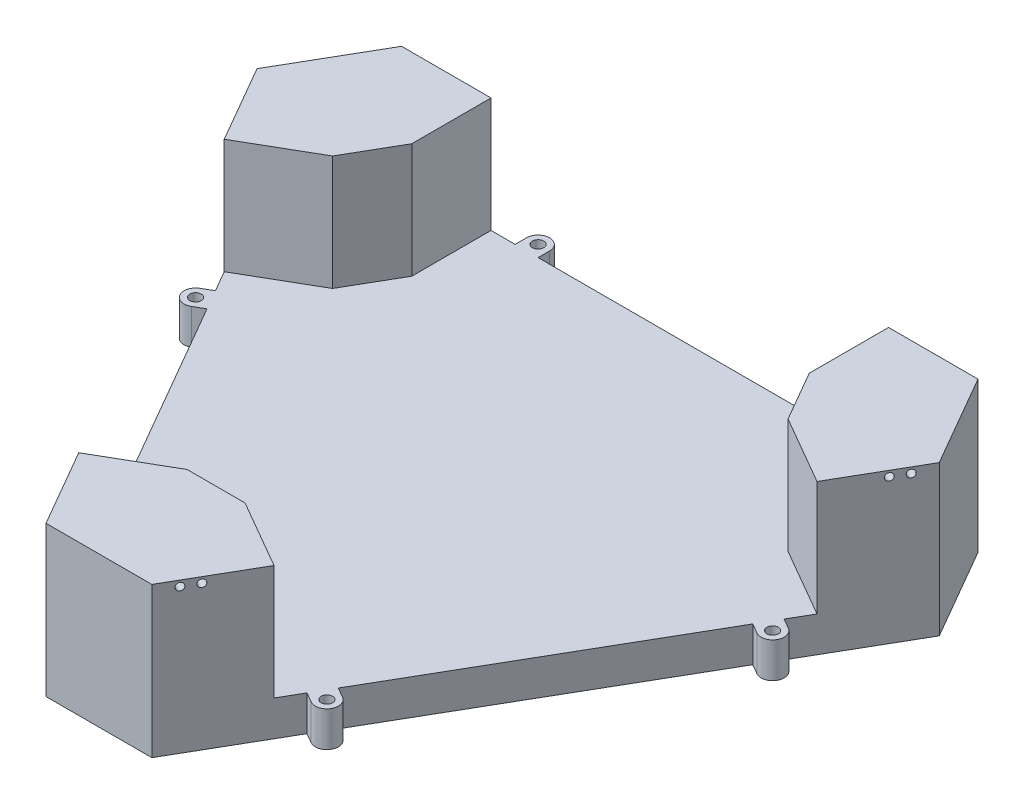
SolidWorks part; units mm, degrees
material "Prusament PETG"
ref_plane "Front Plane" through (0, 0, 0) normal (0, 0, 1) x (1, 0, 0)
ref_plane "Top Plane" through (0, 0, 0) normal (0, 1, 0) x (1, 0, 0)
ref_plane "Right Plane" through (0, 0, 0) normal (1, 0, 0) x (0, 0, -1)
sketch "Sketch1" plane through (0, 0, 0) normal (0, 1, 0) x (1, 0, 0)
  line L3 (-240.2461, 7.855) -> (-236.8299, 13.7721) construction
  line L4 (-120.2366, -188.1733) -> (-7.0596, 7.855) construction
  line L5 (-10.4758, 13.7721) -> (-236.8299, 13.7721) construction
  line L6 (-240.2461, 7.855) -> (-127.0691, -188.1733) construction
  line L7 (-10.4758, 13.7721) -> (-7.0596, 7.855) construction
  line L8 (-120.2366, -188.1733) -> (-127.0691, -188.1733) construction
  line L17 (-236.8299, 13.7721) -> (-10.4758, 13.7721) construction
  line L19 (-278.201, -14.1044) -> (-165.0639, -210.0635) construction
  line L22 (-278.201, -14.1044) -> (-236.7899, 57.6217) construction
  line L24 (-90.4117, 13.7721) -> (-156.894, 13.7721) construction
  line L25 (-156.894, 13.7721) -> (-236.8299, 13.7721) construction
  line L26 (-90.4117, 13.7721) -> (-10.4758, 13.7721) construction
  line L27 (-236.7899, 57.6217) -> (-10.5158, 57.6217) construction
  line L28 (-10.5158, 57.6217) -> (30.8953, -14.1044) construction
  line L29 (30.8953, -14.1044) -> (-82.2418, -210.0635) construction
  line L30 (-82.2418, -210.0635) -> (-165.0639, -210.0635) construction
  line L31 (-236.8299, 13.7721) -> (-156.894, 13.7721) construction
  line L35 (-236.7899, 43.6217) -> (-10.5158, 43.6217)
  line L36 (-240.2461, 7.855) -> (-127.0691, -188.1733) construction
  line L44 (-120.2366, -188.1733) -> (-7.0596, 7.855) construction
  line L47 (-94.3662, -203.0635) -> (18.7709, -7.1044)
  line L48 (18.7709, -7.1044) -> (30.8953, -14.1044) construction
  line L49 (-94.3662, -203.0635) -> (-82.2418, -210.0635) construction
  line L50 (-152.9396, -203.0635) -> (-165.0639, -210.0635) construction
  line L51 (-266.0766, -7.1044) -> (-278.201, -14.1044) construction
  line L52 (-236.7899, 43.6217) -> (-236.7899, 57.6217) construction
  line L53 (-10.5158, 43.6217) -> (-10.5158, 57.6217) construction
  line L54 (18.7709, -7.1044) -> (24.9954, 3.6767)
  line L55 (-10.5158, 43.6217) -> (1.9331, 43.6217)
  line L56 (-94.3662, -203.0635) -> (-100.5906, -213.8446)
  line L57 (-152.9396, -203.0635) -> (-146.7151, -213.8446)
  line L58 (-236.7899, 43.6217) -> (-249.2388, 43.6217)
  line L59 (-266.0766, -7.1044) -> (-272.3011, 3.6767)
  line L60 (-272.3011, 3.6767) -> (-249.2388, 43.6217)
  line L61 (24.9954, 3.6767) -> (1.9331, 43.6217)
  line L62 (-100.5906, -213.8446) -> (-146.7151, -213.8446)
  line L63 (-266.0766, -7.1044) -> (-152.9396, -203.0635)
  circle A0 centre (-123.6529, -55.5154) radius 132.7019 construction
  circle A5 centre (-123.6529, -55.5154) radius 160 construction
  dimension "D1" = 320
  dimension "D3" = 265.4038
  dimension "Distance_of_servo_centre_of_rotation_to_edge" = 14
  dimension "D5" = 82.8221
  dimension "D2" = 30
  dimension "D4" = 90
extrude "Boss-Extrude2" add sketch "Sketch1" along normal blind 5.4 contours L59 L63 L57 L62 L56 L47 L54 L61 L55 L35 L58 L60
sketch "Sketch25" plane through (0, 0, 0) normal (0, -1, 0) x (1, 0, 0)
  line L0 (-272.3011, -3.6767) -> (-249.2388, -43.6217)
  line L1 (-249.2388, -43.6217) -> (1.9331, -43.6217)
  line L2 (1.9331, -43.6217) -> (24.9954, -3.6767)
  line L3 (24.9954, -3.6767) -> (-100.5906, 213.8446)
  line L4 (-100.5906, 213.8446) -> (-146.7151, 213.8446)
  line L5 (-146.7151, 213.8446) -> (-272.3011, -3.6767)
extrude "Boss-Extrude3" add sketch "Sketch25" along normal blind 60
sketch "Sketch26" plane through (-202.6338, 0, 116.9907) normal (-0.866, 0, 0.5) x (0.5, 0, 0.866)
  line L0 (-13.7487, 5.4) -> (-13.7487, -60) construction
  line L1 (111.8373, 5.4) -> (-139.3347, 5.4) construction
  line L2 (111.8373, -60) -> (-139.3347, -60) construction
  line L3 (-38.7487, -15) -> (11.2513, -15)
  line L4 (-38.7487, -15) -> (-38.7487, -55)
  line L5 (11.2513, -15) -> (11.2513, -55)
  line L6 (-38.7487, -55) -> (11.2513, -55)
  line L7 (-38.7487, -15) -> (11.2513, -55) construction
  line L8 (11.2513, -15) -> (-38.7487, -55) construction
  point P6 (-13.7487, -15)
  point P7 (-13.7487, -35)
  dimension "D1" = 50
  dimension "D2" = 40
  dimension "D3" = 5
sketch "Sketch27" plane through (0, 5.4, 0) normal (0, 1, 0) x (1, 0, 0)
  line L0 (-272.3011, 3.6767) -> (-249.2388, 43.6217) construction
  line L1 (-249.2388, 43.6217) -> (1.9331, 43.6217) construction
  line L2 (1.9331, 43.6217) -> (24.9954, 3.6767) construction
  line L3 (24.9954, 3.6767) -> (-100.5906, -213.8446) construction
  line L4 (-100.5906, -213.8446) -> (-146.7151, -213.8446) construction
  line L5 (-146.7151, -213.8446) -> (-272.3011, 3.6767) construction
  line L6 (1.9013, 3.6767) -> (-112.1376, -193.8446)
  line L7 (-112.1376, -193.8446) -> (-135.1681, -193.8446)
  line L8 (-135.1681, -193.8446) -> (-249.2071, 3.6767)
  line L9 (-249.2071, 3.6767) -> (-237.6918, 23.6217)
  line L10 (-237.6918, 23.6217) -> (-9.6139, 23.6217)
  line L11 (-9.6139, 23.6217) -> (1.9013, 3.6767)
  dimension "D1" = 20
sketch "Sketch28" plane through (-202.6338, 0, 116.9907) normal (-0.866, 0, 0.5) x (0.5, 0, 0.866)
  line L0 (95.8884, 2.9) -> (102.8884, 2.9) construction
  line L1 (95.8884, 2.9) -> (86.9395, 2.9) construction
  line L2 (102.8884, 2.9) -> (111.8373, 2.9) construction
  line L3 (111.8373, 5.4) -> (-139.3347, 5.4) construction
  line L4 (111.8373, 5.4) -> (111.8373, -60) construction
  circle A0 centre (95.8884, 2.9) radius 1.6
  circle A1 centre (102.8884, 2.9) radius 1.6
  dimension "D5" = 3.2
  dimension "D1" = 8.9489
  dimension "D2" = 8.9489
  dimension "D3" = 7
  dimension "D4" = 2.5
extrude "Cut-Extrude3" cut sketch "Sketch28" against normal blind 8.2
sketch "Sketch29" plane through (-202.6338, 0, 116.9907) normal (-0.866, 0, 0.5) x (0.5, 0, 0.866)
  line L0 (-130.3858, 2.9) -> (-123.3858, 2.9) construction
  line L1 (-130.3858, 2.9) -> (-139.3347, 2.9) construction
  line L2 (-123.3858, 2.9) -> (-114.4369, 2.9) construction
  line L3 (111.8373, 5.4) -> (-139.3347, 5.4) construction
  line L4 (-139.3347, 5.4) -> (-139.3347, -60) construction
  circle A0 centre (-130.3858, 2.9) radius 1.6
  circle A1 centre (-123.3858, 2.9) radius 1.6
  dimension "D5" = 3.2
  dimension "D1" = 8.9489
  dimension "D2" = 8.9489
  dimension "D3" = 7
  dimension "D4" = 2.5
extrude "Cut-Extrude4" cut sketch "Sketch29" against normal blind 8.2
sketch "Sketch30" plane through (0, 0, -43.6217) normal (0, 0, -1) x (-1, 0, 0)
  line L0 (233.2899, 2.9) -> (240.2899, 2.9) construction
  line L1 (233.2899, 2.9) -> (224.3411, 2.9) construction
  line L2 (240.2899, 2.9) -> (249.2388, 2.9) construction
  line L3 (249.2388, 5.4) -> (-1.9331, 5.4) construction
  line L4 (249.2388, 5.4) -> (249.2388, -60) construction
  line L5 (7.0158, 2.9) -> (14.0158, 2.9) construction
  line L6 (7.0158, 2.9) -> (-1.9331, 2.9) construction
  line L7 (14.0158, 2.9) -> (22.9647, 2.9) construction
  line L8 (-1.9331, 5.4) -> (-1.9331, -60) construction
  circle A0 centre (233.2899, 2.9) radius 1.6
  circle A1 centre (240.2899, 2.9) radius 1.6
  circle A2 centre (7.0158, 2.9) radius 1.6
  circle A3 centre (14.0158, 2.9) radius 1.6
  dimension "D9" = 3.2
  dimension "D10" = 3.2
  dimension "D1" = 8.9489
  dimension "D2" = 8.9489
  dimension "D3" = 7
  dimension "D4" = 2.5
  dimension "D5" = 8.9489
  dimension "D6" = 8.9489
  dimension "D7" = 7
  dimension "D8" = 2.5
extrude "Cut-Extrude5" cut sketch "Sketch30" against normal blind 8.2
sketch "Sketch31" plane through (17.1545, 0, 9.9041) normal (0.866, 0, 0.5) x (0.5, 0, -0.866)
  line L0 (-0.2671, 2.9) -> (6.7329, 2.9) construction
  line L1 (-0.2671, 2.9) -> (-9.216, 2.9) construction
  line L2 (6.7329, 2.9) -> (15.6818, 2.9) construction
  line L3 (15.6818, 5.4) -> (-235.4902, 5.4) construction
  line L4 (15.6818, 5.4) -> (15.6818, -60) construction
  line L5 (-226.5413, 2.9) -> (-219.5413, 2.9) construction
  line L6 (-226.5413, 2.9) -> (-235.4902, 2.9) construction
  line L7 (-219.5413, 2.9) -> (-210.5924, 2.9) construction
  line L8 (-235.4902, 5.4) -> (-235.4902, -60) construction
  circle A0 centre (-0.2671, 2.9) radius 1.6
  circle A1 centre (6.7329, 2.9) radius 1.6
  circle A2 centre (-226.5413, 2.9) radius 1.6
  circle A3 centre (-219.5413, 2.9) radius 1.6
  dimension "D9" = 3.2
  dimension "D10" = 3.2
  dimension "D1" = 8.9489
  dimension "D2" = 8.9489
  dimension "D3" = 7
  dimension "D4" = 2.5
  dimension "D5" = 8.9489
  dimension "D6" = 8.9489
  dimension "D7" = 7
  dimension "D8" = 2.5
extrude "Cut-Extrude6" cut sketch "Sketch31" against normal blind 8.2
sketch "Sketch32" plane through (0, 5.4, 0) normal (0, 1, 0) x (1, 0, 0)
  line L0 (-272.3011, 3.6767) -> (-249.2388, 43.6217) construction
  line L1 (-249.2388, 43.6217) -> (1.9331, 43.6217) construction
  line L2 (1.9331, 43.6217) -> (24.9954, 3.6767) construction
  line L3 (24.9954, 3.6767) -> (-100.5906, -213.8446) construction
  line L4 (-100.5906, -213.8446) -> (-146.7151, -213.8446) construction
  line L5 (-146.7151, -213.8446) -> (-272.3011, 3.6767) construction
  line L6 (-123.6529, -55.5154) -> (-260.77, 23.6492) construction
  line L7 (-123.6529, -55.5154) -> (13.4642, 23.6492) construction
  line L8 (-123.6529, -55.5154) -> (-123.6529, -213.8446) construction
  line L9 (-252.8094, -30.0839) -> (-222.8889, -12.8093)
  line L12 (-136.2863, -162.8093) -> (-166.2068, -180.0839)
  line L13 (-252.8094, -30.0839) -> (-166.2068, -180.0839)
  line L14 (5.5036, -30.0839) -> (-24.4169, -12.8093)
  line L17 (-111.0194, -162.8093) -> (-81.0989, -180.0839)
  line L18 (5.5036, -30.0839) -> (-81.0989, -180.0839)
  line L19 (-37.0503, 43.6217) -> (-210.2554, 43.6217)
  line L20 (-210.2554, 9.0725) -> (-210.2554, 43.6217)
  line L23 (-37.0503, 43.6217) -> (-37.0503, 9.0725)
  line L24 (-222.8889, -12.8093) -> (-210.2554, 9.0725)
  line L25 (-37.0503, 9.0725) -> (-24.4169, -12.8093)
  line L26 (-111.0194, -162.8093) -> (-136.2863, -162.8093)
  circle A1 centre (-123.6529, -55.5154) radius 160 construction
  dimension "D3" = 38.9834
extrude "Cut-Extrude7" cut sketch "Sketch32" against normal blind 50
sketch "Sketch33" plane through (0, -44.6, 0) normal (0, 1, 0) x (1, 0, 0)
  line L0 (-37.0503, 43.6217) -> (-210.2554, 43.6217) construction
  line L1 (-57.5509, 43.6217) -> (-47.5509, 43.6217)
  line L2 (-57.5509, 43.6217) -> (-57.5509, 48.6217)
  line L4 (-47.5509, 43.6217) -> (-47.5509, 48.6217)
  line L5 (-123.6529, 43.6217) -> (-123.6529, -55.5154) construction
  line L6 (-123.6529, -55.5154) -> (-37.7976, -105.0839) construction
  line L7 (-81.0989, -180.0839) -> (5.5036, -30.0839) construction
  line L8 (-123.6529, -55.5154) -> (-209.5081, -105.0839) construction
  line L9 (-252.8094, -30.0839) -> (-166.2068, -180.0839) construction
  line L10 (-123.6529, -55.5154) -> (13.4642, 23.6492) construction
  line L11 (24.9954, 3.6767) -> (1.9331, 43.6217) construction
  line L12 (-123.6529, -55.5154) -> (-123.6529, -213.8446) construction
  line L13 (-100.5906, -213.8446) -> (-146.7151, -213.8446) construction
  line L14 (-123.6529, -55.5154) -> (-260.77, 23.6492) construction
  line L15 (-272.3011, 3.6767) -> (-249.2388, 43.6217) construction
  line L16 (-189.7548, 43.6217) -> (-189.7548, 48.6217)
  line L17 (-189.7548, 43.6217) -> (-199.7548, 43.6217)
  line L18 (-199.7548, 43.6217) -> (-199.7548, 48.6217)
  line L19 (-242.5591, -47.838) -> (-247.5591, -39.1777)
  line L20 (-247.5591, -39.1777) -> (-251.8892, -41.6777)
  line L21 (-242.5591, -47.838) -> (-246.8892, -50.338)
  line L22 (-176.4571, -162.3299) -> (-180.7872, -164.8299)
  line L23 (-171.4571, -170.9902) -> (-175.7872, -173.4902)
  line L24 (-176.4571, -162.3299) -> (-171.4571, -170.9902)
  line L25 (-70.8486, -162.3299) -> (-75.8486, -170.9902)
  line L26 (-75.8486, -170.9902) -> (-71.5185, -173.4902)
  line L27 (-70.8486, -162.3299) -> (-66.5185, -164.8299)
  line L28 (-4.7466, -47.838) -> (-0.4165, -50.338)
  line L29 (0.2534, -39.1777) -> (4.5835, -41.6777)
  line L30 (-4.7466, -47.838) -> (0.2534, -39.1777)
  circle A0 centre (-123.6529, -55.5154) radius 160 construction
  arc A1 (-57.5509, 48.6217) -> (-47.5509, 48.6217) centre (-52.5509, 48.6217) cw
  circle A2 centre (-52.5509, 48.6217) radius 2.5
  circle A3 centre (-194.7548, 48.6217) radius 2.5
  arc A4 (-189.7548, 48.6217) -> (-199.7548, 48.6217) centre (-194.7548, 48.6217) ccw
  circle A5 centre (-249.3892, -46.0078) radius 2.5
  arc A6 (-246.8892, -50.338) -> (-251.8892, -41.6777) centre (-249.3892, -46.0078) cw
  circle A7 centre (-178.2872, -169.1601) radius 2.5
  arc A8 (-180.7872, -164.8299) -> (-175.7872, -173.4902) centre (-178.2872, -169.1601) ccw
  circle A9 centre (-69.0185, -169.1601) radius 2.5
  arc A10 (-66.5185, -164.8299) -> (-71.5185, -173.4902) centre (-69.0185, -169.1601) cw
  circle A11 centre (2.0835, -46.0078) radius 2.5
  arc A12 (-0.4165, -50.338) -> (4.5835, -41.6777) centre (2.0835, -46.0078) ccw
  dimension "D2" = 5
  dimension "D3" = 5
  dimension "D1" = 5
extrude "Boss-Extrude4" add sketch "Sketch33" against normal up to surface (15.4 mm away) up to face at (-123.6529, -60, 55.5154)
equation "\"Hexagon_long_side_length\"= 2 * \"Matlab_Diameter_enclosing_circle\" / 2 * sin ( \"theta_long_side\" / 2 )"
equation "\"Hexagon_short_side_length\"= 2 * \"Matlab_Diameter_enclosing_circle\" / 2 * sin ( \"theta_short_side\" / 2 )"
equation "\"Width_upper_lower_shell\"= 0.0054"
equation "\"D1@Boss-Extrude2\"=\"Width_upper_lower_shell\""
equation "\"holes_distance_from edge\"= \"Hexagon_short_side_length\" / 4m"
equation "\"holes_distance_from_eachother\"= 0.01"
equation "\"holes_distance_from_top\"= \"Width_upper_lower_shell\" / 2"
equation "\"theta_short_side\"= 30deg"
equation "\"theta_long_side\"= 120deg - \"theta_short_side\""
equation "\"Diametre_enclosing_circle\"= \"Matlab_Diameter_enclosing_circle\" * 0.75"
equation "\"Radius_enclosing_circle\"= \"Diametre_enclosing_circle\" / 2"
equation "\"Matlab_Diameter_enclosing_circle\"= 320mm"
equation "\"Distance_of_servo_centre_of_rotation_to_edge\"= 1.4cm"
equation "\"D1@Sketch1\"=\"Matlab_Diameter_enclosing_circle\""
equation "\"D2@Sketch1\" = \"theta_short_side\""
equation "\"Height_Lower_shell_stat_Piv\"= 0.06"
equation "\"D1@Boss-Extrude3\"=\"Height_Lower_shell_stat_Piv\""
equation "\"Batterie_Hole_Length\"= 16cm"
equation "\"Batterie_Hole_Width\"= 5cm"
equation "\"Batterie_Hole_Height\"= 4cm"
equation "\"D1@Sketch26\"=\"Batterie_Hole_Width\""
equation "\"D2@Sketch26\"=\"Batterie_Hole_Height\""
equation "\"3D_print_long_Side_extrusion\"= 10cm"
equation "\"3D_print_short_Side_extrusion\"= 4cm"
equation "\"3D_print_distance_from_edge\"= 2cm"
